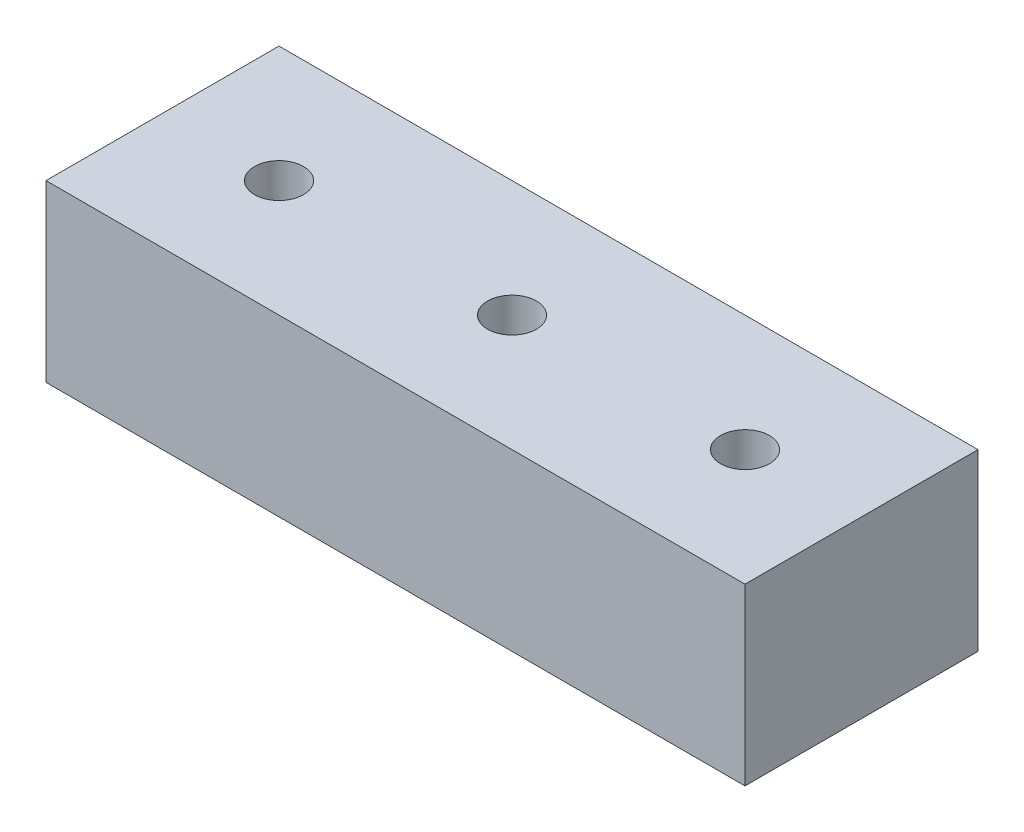
SolidWorks part; units mm, degrees
ref_plane "前视基准面" through (0, 0, 0) normal (0, 0, 1) x (1, 0, 0)
ref_plane "上视基准面" through (0, 0, 0) normal (0, 1, 0) x (1, 0, 0)
ref_plane "右视基准面" through (0, 0, 0) normal (1, 0, 0) x (0, 0, -1)
sketch "草图1" plane through (0, 0, 0) normal (0, 1, 0) x (1, 0, 0)
  line L1 (0, 0) -> (60, 0)
  line L2 (0, 0) -> (0, -20)
  line L3 (0, -20) -> (60, -20)
  line L4 (60, 0) -> (60, -20)
  circle A0 centre (10, -10) radius 2.1
  circle A1 centre (30, -10) radius 2.1
  circle A2 centre (50, -10) radius 2.1
  point P13 (20.6237, -5.2668)
  dimension "D3" = 10
  dimension "D5" = 4.2
  dimension "D1" = 20
  dimension "D2" = 60
  dimension "D4" = 10
  dimension "D7" = 20
  dimension "D6" = 3
extrude "凸台-拉伸1" add sketch "草图1" along normal blind 15
